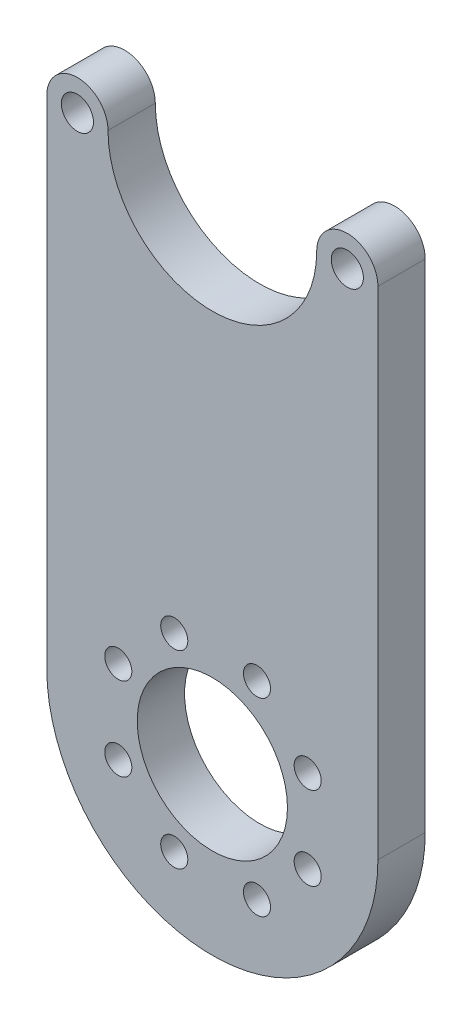
SolidWorks part; units mm, degrees
ref_plane "前视基准面" through (0, 0, 0) normal (0, 0, 1) x (1, 0, 0)
ref_plane "上视基准面" through (0, 0, 0) normal (0, 1, 0) x (1, 0, 0)
ref_plane "右视基准面" through (0, 0, 0) normal (1, 0, 0) x (0, 0, -1)
sketch "草图1" plane through (0, 0, 0) normal (0, 0, 1) x (1, 0, 0)
  line L2 (-22.8429, 35.5738) -> (-22.8429, -16.9262)
  line L4 (12.1571, 35.5738) -> (12.1571, -16.9262)
  arc A1 (-22.8429, -16.9262) -> (12.1571, -16.9262) centre (-5.3429, -16.9262) ccw
  circle A2 centre (-5.3429, -16.9262) radius 7.94
  arc A3 (-16.3728, 35.5738) -> (5.687, 35.5738) centre (-5.3429, 35.5738) ccw
  arc A4 (5.687, 35.5738) -> (12.1571, 35.5738) centre (8.922, 35.5738) cw
  arc A5 (-22.8429, 35.5738) -> (-16.3728, 35.5738) centre (-19.6079, 35.5738) cw
  circle A6 centre (-19.6079, 35.5738) radius 1.6979
  circle A7 centre (8.922, 35.5738) radius 1.6979
  circle A8 centre (-9.3691, -6.9449) radius 1.4313
  circle A9 centre (-15.2861, -12.6985) radius 1.4313
  circle A10 centre (-0.6251, -26.9401) radius 1.4313
  circle A11 centre (-15.2861, -21.4845) radius 1.4313
  circle A12 centre (-9.3691, -26.9401) radius 1.4313
  circle A13 centre (-0.6251, -6.9449) radius 1.4313
  circle A14 centre (4.7338, -12.6985) radius 1.4313
  circle A15 centre (4.7338, -21.4845) radius 1.4313
  point P19 (-13.2829, -8.9862)
  point P20 (-5.3429, -27.8042)
  point P23 (-15.2404, -16.9262)
  point P26 (-13.2829, -24.8662)
  point P29 (3.5094, -8.9862)
  point P30 (4.9094, -16.9262)
  point P31 (-5.3429, -27.2246)
  point P32 (-13.2829, -24.9462)
  point P33 (4.0187, -23.5739)
  point P36 (-14.4088, -12.6985)
  point P37 (-9.3691, -6.9449)
  point P38 (-0.6251, -6.9449)
  point P41 (5.687, -19.0479)
  point P42 (-14.4088, -21.4845)
  point P43 (-9.3691, -25.5827)
  point P44 (-0.6251, -25.5827)
  point P45 (4.7338, -21.4845)
  point P46 (0, 0)
  point P47 (4.7338, -12.6985)
  point P48 (-15.2861, -12.6985)
  point P49 (-9.8548, -26.5328)
  point P50 (-0.6251, -26.9401)
  point P51 (-15.2861, -21.4845)
  point P52 (-9.3691, -26.9401)
  point P53 (-15.2861, -21.4845)
  point P54 (-15.2861, -12.6985)
  point P55 (-9.3691, -6.9449)
  point P56 (-0.6251, -6.9449)
  point P57 (4.7338, -12.6985)
  dimension "D1" = 15.88
  dimension "D2" = 35
extrude "凸台-拉伸1" add sketch "草图1" along normal blind 5
